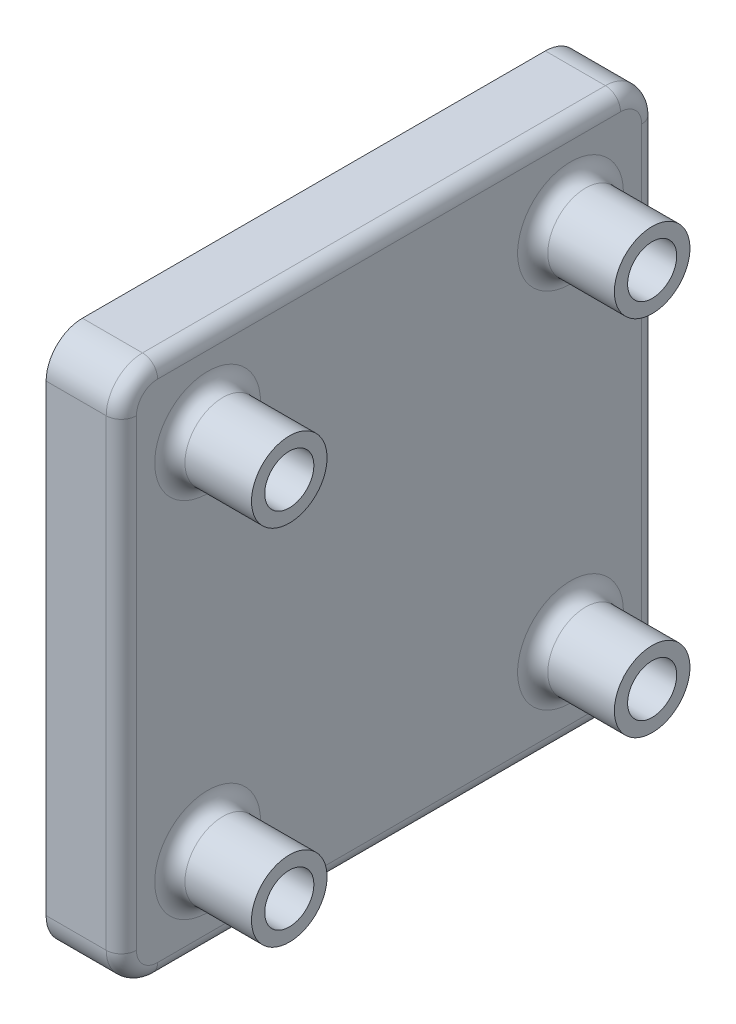
SolidWorks part; units mm, degrees
ref_plane "Front Plane" through (0, 0, 0) normal (1, 0, 0) x (0, 1, 0)
ref_plane "Top Plane" through (0, 0, 0) normal (0, 0, 1) x (0, 1, 0)
ref_plane "Right Plane" through (0, 0, 0) normal (0, 1, 0) x (-1, 0, 0)
sketch "Sketch1" plane through (0, 0, 0) normal (1, 0, 0) x (0, 1, 0)
  circle A0 centre (40.194, 139.9366) radius 1.25 construction
  circle A1 centre (40.194, 163.9366) radius 1.25 construction
  circle A2 centre (16.194, 163.9366) radius 1.25 construction
  circle A3 centre (16.194, 139.9366) radius 1.25 construction
  circle A4 centre (40.194, 139.9366) radius 1.25
  circle A5 centre (40.194, 163.9366) radius 1.25
  circle A6 centre (16.194, 163.9366) radius 1.25
  circle A7 centre (16.194, 139.9366) radius 1.25
sketch "Sketch2" plane through (0, 0, 0) normal (1, 0, 0) x (0, 1, 0)
  line L0 (10.4855, 169.6451) -> (45.9025, 134.2281) construction
  line L1 (10.4855, 169.6451) -> (45.9025, 169.6451)
  line L2 (10.4855, 169.6451) -> (10.4855, 134.2281)
  line L3 (10.4855, 134.2281) -> (45.9025, 134.2281)
  line L4 (45.9025, 169.6451) -> (45.9025, 134.2281)
  line L5 (45.9025, 169.6451) -> (10.4855, 134.2281) construction
  circle A8 centre (16.194, 163.9366) radius 1.625
  circle A9 centre (40.194, 163.9366) radius 1.625
  circle A10 centre (40.194, 139.9366) radius 1.625
  circle A11 centre (16.194, 139.9366) radius 1.625
  dimension "D1" = 3.25
extrude "Boss-Extrude1" add sketch "Sketch2" along normal blind 4.975
sketch "Sketch3" plane through (4.975, 0, 0) normal (1, 0, 0) x (0, 1, 0)
  circle A0 centre (16.194, 163.9366) radius 2.5
  circle A1 centre (40.194, 163.9366) radius 2.5
  circle A2 centre (40.194, 139.9366) radius 2.5
  circle A3 centre (16.194, 139.9366) radius 2.5
  circle A12 centre (16.194, 139.9366) radius 1.625 construction
  circle A13 centre (40.194, 139.9366) radius 1.625 construction
  circle A14 centre (40.194, 163.9366) radius 1.625 construction
  circle A15 centre (16.194, 163.9366) radius 1.625 construction
  circle A16 centre (16.194, 139.9366) radius 1.625
  circle A17 centre (40.194, 139.9366) radius 1.625
  circle A18 centre (40.194, 163.9366) radius 1.625
  circle A19 centre (16.194, 163.9366) radius 1.625
  dimension "D1" = 5
extrude "Boss-Extrude2" add sketch "Sketch3" along normal blind 5.4
fillet "Fillet1" radius 2.4 4 edges at (2.4875, 45.9025, 169.6451) (2.4875, 45.9025, 134.2281) (2.4875, 10.4855, 134.2281) (2.4875, 10.4855, 169.6451)
fillet "Fillet2" radius 1 12 edges at (4.975, 16.194, 161.4366) (4.975, 45.1996, 134.931) (4.975, 28.194, 134.2281) (4.975, 11.1884, 134.931) (4.975, 10.4855, 151.9366) (4.975, 11.1884, 168.9421) (4.975, 28.194, 169.6451) (4.975, 45.1996, 168.9421) (4.975, 45.9025, 151.9366) (4.975, 40.194, 161.4366) (4.975, 40.194, 137.4366) (4.975, 16.194, 137.4366)
